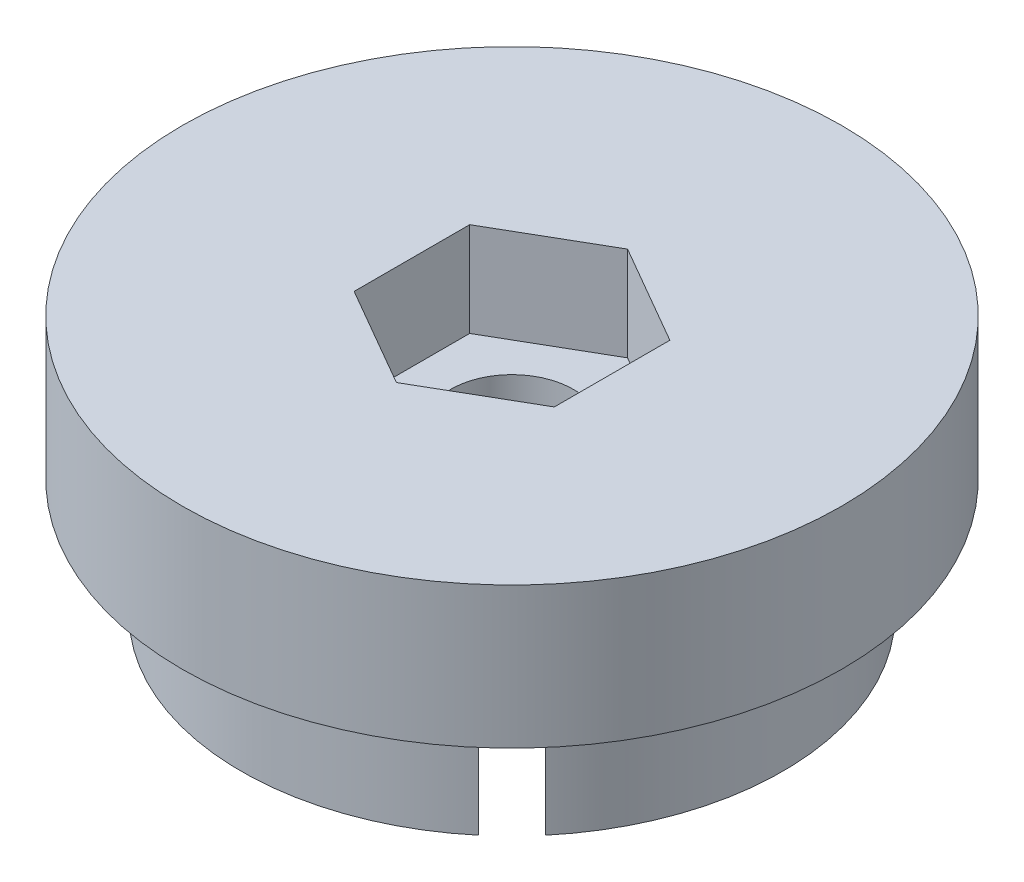
SolidWorks part; units mm, degrees
ref_plane "Front Plane" through (0, 0, 0) normal (0, 0, 1) x (1, 0, 0)
ref_plane "Top Plane" through (0, 0, 0) normal (0, 1, 0) x (1, 0, 0)
ref_plane "Right Plane" through (0, 0, 0) normal (1, 0, 0) x (0, 0, -1)
sketch "Sketch3" plane through (0, 0, 0) normal (0, 1, 0) x (1, 0, 0)
  line L1 (3, -3) -> (-3, -3)
  line L2 (3, -3) -> (3, 3)
  line L3 (3, 3) -> (-3, 3)
  line L4 (-3, -3) -> (-3, 3)
  line L5 (3, -3) -> (-3, 3) construction
  line L6 (3, 3) -> (-3, -3) construction
  circle A2 centre (0, 0) radius 2.6
  dimension "D1" = 5.2
  dimension "D3" = 6
extrude "Base" add sketch "Sketch3" against normal blind 5
sketch "Sketch8" plane through (0, 0, 0) normal (0, 1, 0) x (1, 0, 0)
  circle A0 centre (0, 0) radius 14
  circle A1 centre (0, 0) radius 2.6 construction
  circle A2 centre (0, 0) radius 2.6
  dimension "D1" = 28
extrude "Bloc" add sketch "Sketch8" along normal blind 6
sketch "Sketch4" plane through (0, 6, 0) normal (0, 1, 0) x (1, 0, 0)
  line L1 (0, 4.9075) -> (-4.25, 2.4537)
  line L2 (-4.25, 2.4537) -> (-4.25, -2.4537)
  line L3 (-4.25, -2.4537) -> (0, -4.9075)
  line L4 (0, -4.9075) -> (4.25, -2.4537)
  line L5 (4.25, -2.4537) -> (4.25, 2.4537)
  line L6 (4.25, 2.4537) -> (0, 4.9075)
  circle A0 centre (0, 0) radius 4.25 construction
  dimension "D2" = 8.5
extrude "Nut_place" cut sketch "Sketch4" against normal blind 4
sketch "Sketch9" plane through (0, 0, 0) normal (0, -1, 0) x (1, 0, 0)
  line L0 (-5.5392, 4.125) -> (-8.808, 7.3938)
  line L1 (5.5392, -5.5392) -> (-5.5392, -5.5392) construction
  line L2 (5.5392, -5.5392) -> (5.5392, 5.5392) construction
  line L3 (5.5392, 5.5392) -> (-5.5392, 5.5392) construction
  line L4 (-5.5392, -5.5392) -> (-5.5392, 5.5392) construction
  line L5 (5.5392, -5.5392) -> (-5.5392, 5.5392) construction
  line L6 (5.5392, 5.5392) -> (-5.5392, -5.5392) construction
  line L7 (-7.3938, 8.808) -> (-4.125, 5.5392)
  line L8 (8.808, 7.3938) -> (5.5392, 4.125)
  line L9 (4.125, 5.5392) -> (7.3938, 8.808)
  line L10 (7.3938, -8.808) -> (4.125, -5.5392)
  line L11 (5.5392, -4.125) -> (8.808, -7.3938)
  line L12 (-8.808, -7.3938) -> (-5.5392, -4.125)
  line L13 (-4.125, -5.5392) -> (-7.3938, -8.808)
  line L14 (-5.5392, 4.125) -> (-5.5392, -4.125)
  line L15 (-4.125, -5.5392) -> (4.125, -5.5392)
  line L16 (5.5392, -4.125) -> (5.5392, 4.125)
  line L17 (4.125, 5.5392) -> (-4.125, 5.5392)
  circle A0 centre (0, 0) radius 11.5
  circle A1 centre (0, 0) radius 14
  circle A2 centre (0, 0) radius 14 construction
  point P28 (0, 0)
  dimension "D3" = 8.25
  dimension "D4" = 2
  dimension "D5" = 1
  dimension "D1" = 0
  dimension "D2" = 2.5
  dimension "D6" = 4
extrude "Reinforcement" add sketch "Sketch9" along normal up to surface (5 mm away) contours L11 A0 L8 L16 | L13 A0 L10 L15 | L0 A0 L12 L14 | L9 A0 L7 L17 up to face at (0, -5, 2.6)
